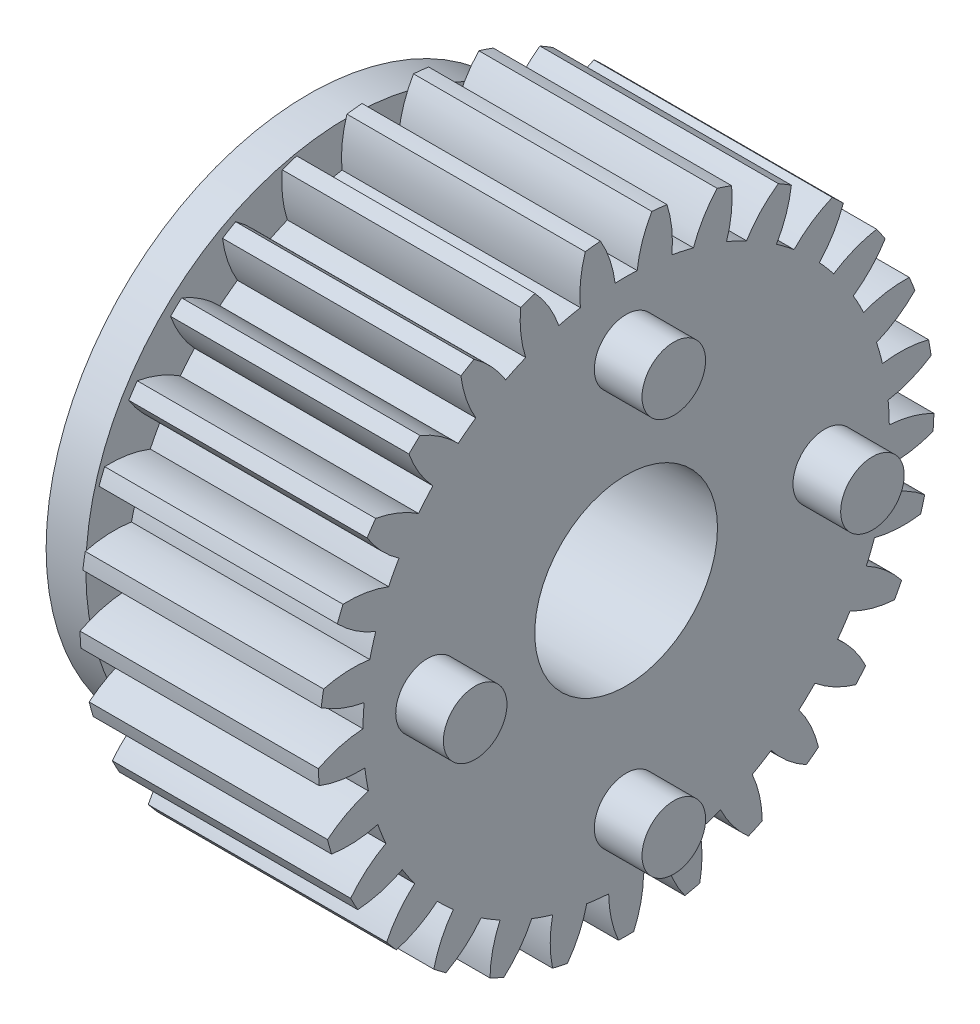
SolidWorks part; units mm, degrees
ref_plane "Plane1" through (0, 0, 0) normal (0, 0, 1) x (1, 0, 0)
ref_plane "Plane2" through (0, 0, 0) normal (0, 1, 0) x (1, 0, 0)
ref_plane "Plane3" through (0, 0, 0) normal (1, 0, 0) x (0, 0, -1)
other "Configuration Table"
sketch "HoldingSke" plane through (0, 0, 0) normal (0, 1, 0) x (1, 0, 0)
  line L0 (0, 0) -> (0.3498, -0.1939)
  line L1 (-15, 0) -> (100, 0) construction
  line L2 (0, 0) -> (-2.1039, 2.3779)
  line L3 (0, 0) -> (-11.863, 4.5341)
  line L4 (0, 0) -> (7.5532, 4.1868)
  line L5 (0, 0) -> (-46.8476, -17.4728)
  line L6 (0, 0) -> (-24.8689, -16.7791)
  line L7 (-2.1039, 2.3779) -> (8.6586, 51.2059)
  line L8 (-76.2, 54.61) -> (-73.9, 54.61)
  line L9 (-67.7845, 28.3722) -> (-49.3413, 33.142)
  line L10 (-76.2, 71.12) -> (104.1128, 71.12)
  line L11 (0, 0) -> (-30, 0)
  line L12 (-76.2, 101.6) -> (-76.113, 101.6)
  line L13 (24.9733, 27.94) -> (52.9518, 28.4284)
  line L14 (24.9733, 27.94) -> (24.9743, 27.94)
  line L15 (24.9733, 27.94) -> (100.4006, 29.5858)
  line L16 (-63.627, -2.5) -> (-12.827, -2.5)
  circle A0 centre (0, 0) radius 6
  circle A1 centre (0, 0) radius 33.124
  circle A2 centre (0, 0) radius 37.5
  circle A3 centre (0, 0) radius 6
  dimension "MHD" = 66.248
  dimension "Hub_dia" = 75
  dimension "Bore" = 12
  dimension "MBD" = 12
  dimension "Num_teeth" = 29
  dimension "Pitch" = 0.4
  dimension "Overall_len" = 50
  dimension "Show_teeth" = 29
  dimension "Thickness" = 30
  dimension "OAL" = 50.0001
  dimension "T_dim" = 2.3
  dimension "Ap" = 14.5
  dimension "H" = 19.05
  dimension "Pitch_radius" = 180.3128
  dimension "Width" = 30
  dimension "Backlash" = 0.087
  dimension "Addendum_fac" = 1
  dimension "Dedendum_fac" = 1.25
  dimension "Clearance_fac" = 0.25
  dimension "Dedendum_add" = 0.001
  dimension "Module" = 2.5
sketch "BasProSke" plane through (0, 0, 0) normal (0, 1, 0) x (1, 0, 0)
  line L0 (-10, 0) -> (60, 0) construction
  line L1 (0, 0) -> (0, 38.75)
  line L2 (0, 0) -> (30, 0)
  line L3 (30, 0) -> (30, 38.75)
  line L4 (30, 38.75) -> (0, 38.75)
  dimension "Thickness" = 30
  dimension "Diameter" = 77.5
revolve "Base-Revolve" add sketch "BasProSke" angle 360 about L0
sketch "TooCutSke" plane through (0, 0, 0) normal (1, 0, 0) x (0, 0, -1)
  line L1 (0, 0) -> (0, 107) construction
  line L2 (0, 0) -> (-2.1148, 36.1883) construction
  line L3 (0, 0) -> (-7.8288, 71.9851) construction
  line L4 (-2.1148, 36.1883) -> (-3.9144, 35.9925) construction
  arc A0 (1.3883, 33.0949) -> (-1.3883, 33.0949) centre (0, 0) ccw
  arc A1 (3.2498, 38.639) -> (-3.2498, 38.639) centre (0, 0) ccw
  circle A2 centre (0, 0) radius 36.25 construction
  circle A3 centre (0, 0) radius 35.0954 construction
  arc A4 (-1.3883, 33.0949) -> (-3.2498, 38.639) centre (-15.7825, 31.3464) ccw
  arc A5 (3.2498, 38.639) -> (1.3883, 33.0949) centre (15.7825, 31.3464) ccw
  dimension "Root_dia" = 66.248
  dimension "Overcut_dia" = 77.5508
  dimension "Pitch_dia" = 72.5
  dimension "Base_dia" = 70.1907
  dimension "Flank_rad" = 14.5
  dimension "Half_ang" = 6.207
  dimension "Half_CT" = 1.8103
extrude "ToothCut" cut sketch "TooCutSke" along normal through all
fillet "Breaks" [suppressed] radius 0.05
fillet "RootFillets" [suppressed] radius 0.626
pattern_circular "TeethCuts" count 29 every 12.414 about axis through (-10, 0, 0) along (1, 0, 0) of "ToothCut", "RootFillets", "Breaks"
sketch "HubNeaOneSke" plane through (0, 0, 0) normal (-1, 0, 0) x (0, 0, 1)
  circle A0 centre (0, 0) radius 33.124
  dimension "Diameter" = 66.248
extrude "HubNearOne" [suppressed] add sketch "HubNeaOneSke" along normal blind 20.0001
sketch "HubNeaBotSke" plane through (0, 0, 0) normal (-1, 0, 0) x (0, 0, 1)
  circle A0 centre (0, 0) radius 33.124
  dimension "Diameter" = 66.248
extrude "HubNearBoth" [suppressed] add sketch "HubNeaBotSke" along normal blind 10
ref_plane "FarPln" through (30, 0, 0) normal (1, 0, 0) x (0, 0, -1)
sketch "HubFarSke" plane through (30, 0, 0) normal (1, 0, 0) x (0, 0, -1)
  circle A0 centre (0, 0) radius 33.124
  dimension "Diameter" = 66.248
extrude "HubFar" [suppressed] add sketch "HubFarSke" along normal blind 10
sketch "BorSke" plane through (0, 0, 0) normal (1, 0, 0) x (0, 0, -1)
  circle A0 centre (0, 0) radius 6
  dimension "Diameter" = 12
extrude "Bore" cut sketch "BorSke" along normal mid plane 100.0001
sketch "KeySke" plane through (0, 0, 0) normal (1, 0, 0) x (0, 0, -1)
  line L0 (-2.5, 0) -> (-2.5, 8.3)
  line L1 (-2.5, 8.3) -> (2.5, 8.3)
  line L2 (2.5, 8.3) -> (2.5, 0)
  line L3 (0, 0) -> (0, 34) construction
  line L4 (-2.5, 0) -> (2.5, 0)
  dimension "Offset" = 8.3
  dimension "Width" = 5
extrude "Keyway" [suppressed] cut sketch "KeySke" along normal mid plane 100.0001
pattern_circular "Keyway2" [suppressed] count 2 every 90 about axis through (-10, 0, 0) along (1, 0, 0)
sketch "Esquisse1" plane through (30, 0, 0) normal (1, 0, 0) x (0, 0, -1)
  circle A0 centre (0, 0) radius 25
  circle A1 centre (0, 25) radius 4
  circle A2 centre (-25, 0) radius 4
  circle A3 centre (25, 0) radius 4
  circle A4 centre (0, -25) radius 4
  dimension "D1" = 8
extrude "Boss.-Extru.1" add sketch "Esquisse1" along normal blind 6 contours A1 | A2 | A4 | A3
sketch "Esquisse2" plane through (30, 0, 0) normal (1, 0, 0) x (0, 0, -1)
  circle A0 centre (0, 0) radius 11.5
extrude "Enlèv. mat.-Extru.1" cut sketch "Esquisse2" against normal through all
sketch "Esquisse3" plane through (0, 0, 0) normal (-1, 0, 0) x (0, 0, 1)
  circle A0 centre (0, 0) radius 23
  circle A1 centre (0, 0) radius 8
extrude "Boss.-Extru.2" add sketch "Esquisse3" along normal blind 5 contours A0 | A1
sketch "Esquisse4" plane through (-5, 0, 0) normal (-1, 0, 0) x (0, 0, 1)
  circle A0 centre (0, 0) radius 33
  circle A1 centre (0, 0) radius 8
extrude "Boss.-Extru.3" add sketch "Esquisse4" along normal blind 5
equation "' \"Module@HoldingSke\" = 6.35"
equation "' \"Num_teeth@HoldingSke\" = 12"
equation "' \"Ap@HoldingSke\" =  20"
equation "' \"Ap@HoldingSke\" = 20"
equation "' \"Width@HoldingSke\" = 0.5 * 25.4"
equation "' \"Hub_dia@HoldingSke\"= 1 * 25.4"
equation "' \"Hub_dia@HoldingSke\" = 1 * 25.4"
equation "' \"Overall_len@HoldingSke\" = 1.0 * 25.4"
equation "' \"Bore@HoldingSke\" = 0.75 * 25.4"
equation "' \"T_dim@HoldingSke\" = 0.1 * 25.4"
equation "' \"Width@KeySke\" = 0.25 * 25.4"
equation "' \"Show_teeth@HoldingSke\" = 13"
equation "' \"Backlash@HoldingSke\" = 0.009 * 25.4"
equation "' \"Addendum_fac@HoldingSke\" = 1.0"
equation "' \"Dedendum_fac@HoldingSke\" = 1.25"
equation "' \"Dedendum_add@HoldingSke\" = 0.00005 * 25.4"
equation "' \"Clearance_fac@HoldingSke\" = 0.25"
equation "\"Pitch@HoldingSke\" = 1 / \"Module@HoldingSke\""
equation "\"Overcut_dia@TooCutSke\" = (\"Num_teeth@HoldingSke\" + 2 * \"Addendum_fac@HoldingSke\") / \"Pitch@HoldingSke\" + 0.002 * 25.4"
equation "\"Pitch_dia@TooCutSke\" = \"Num_teeth@HoldingSke\" / \"Pitch@HoldingSke\""
equation "\"Base_dia@TooCutSke\" = \"Num_teeth@HoldingSke\" / \"Pitch@HoldingSke\" * cos((\"Ap@HoldingSke\"  * 3.14159265 / 180))"
equation "\"Root_dia@TooCutSke\" = (\"Num_teeth@HoldingSke\" + 2) / \"Pitch@HoldingSke\" - 2 * (\"Addendum_fac@HoldingSke\" + \"Dedendum_fac@HoldingSke\") / \"Pitch@HoldingSke\" - \"Dedendum_add@HoldingSke\" * 2"
equation "\"Half_ang@TooCutSke\" = 180 / \"Num_teeth@HoldingSke\""
equation "\"Half_CT@TooCutSke\" = \"Num_teeth@HoldingSke\" / \"Pitch@HoldingSke\" * sin((3.14159265 / 2 / \"Num_teeth@HoldingSke\")) / 2 - 7 * \"Backlash@HoldingSke\" / 4"
equation "\"Flank_rad@TooCutSke\" = \"Num_teeth@HoldingSke\" / \"Pitch@HoldingSke\" / 5"
equation "\"Radius@RootFillets\" = \"Clearance_fac@HoldingSke\" / \"Pitch@HoldingSke\" + \"Dedendum_add@HoldingSke\""
equation "\"Break_rad@Breaks\" = 0.02 / \"Pitch@HoldingSke\""
equation "\"Thickness@HoldingSke\" = \"Width@HoldingSke\""
equation "\"OAL@HoldingSke\" = \"Thickness@HoldingSke\""
equation "\"MHD@HoldingSke\" = (\"Num_teeth@HoldingSke\" + 2) / \"Pitch@HoldingSke\" - 2 * (\"Addendum_fac@HoldingSke\" + \"Dedendum_fac@HoldingSke\")  / \"Pitch@HoldingSke\" - \"Dedendum_add@HoldingSke\" * 2"
equation "\"MBD@HoldingSke\" = (\"Num_teeth@HoldingSke\" + 2) / \"Pitch@HoldingSke\" - 2 * (\"Addendum_fac@HoldingSke\" + \"Dedendum_fac@HoldingSke\")  / \"Pitch@HoldingSke\" - \"Dedendum_add@HoldingSke\" * 2 - 0.002 * 25.4"
equation "\"MHD@HoldingSke\" = ((sgn( \"MHD@HoldingSke\" - \"Hub_dia@HoldingSke\" )-1)*( \"MHD@HoldingSke\" - \"Hub_dia@HoldingSke\" ))/-2+ \"Hub_dia@HoldingSke\""
equation "\"MBD@HoldingSke\" = ((sgn( \"MBD@HoldingSke\" - \"Bore@HoldingSke\" )-1)*( \"MBD@HoldingSke\" - \"Bore@HoldingSke\" ))/-2+ \"Bore@HoldingSke\""
equation "\"OAL@HoldingSke\" = ((sgn( \"OAL@HoldingSke\" - \"Overall_len@HoldingSke\" )+1)*( \"OAL@HoldingSke\" - \"Overall_len@HoldingSke\" ))/2 + \"Overall_len@HoldingSke\" + 0.000002 * 25.4"
equation "\"Num_teeth@TeethCuts\" = int( \"Show_teeth@HoldingSke\" ) + 1"
equation "\"Num_teeth@TeethCuts\" = ((sgn( \"Num_teeth@TeethCuts\" - \"Num_teeth@HoldingSke\" )-1)*( \"Num_teeth@TeethCuts\" - \"Num_teeth@HoldingSke\" ))/-2+ \"Num_teeth@HoldingSke\""
equation "\"Num_teeth@TeethCuts\" = ((sgn( \"Num_teeth@TeethCuts\" - 2.0)+1)*( \"Num_teeth@TeethCuts\" - 2.0))/2 +2.0"
equation "\"Angle@TeethCuts\" = 360.0 / \"Num_teeth@HoldingSke\""
equation "\"Diameter@BasProSke\" = (\"Num_teeth@HoldingSke\" + 2 * \"Addendum_fac@HoldingSke\") / \"Pitch@HoldingSke\""
equation "\"Thickness@BasProSke\"  = \"Thickness@HoldingSke\""
equation "' \"Fillet_rad@BasProSke\" =  \"Thickness@HoldingSke\" * 0.05"
equation "' \"Fillet_rad@BasProSke\" = \"Thickness@HoldingSke\" * 0.05"
equation "\"MHD@HoldingSke\" = ((sgn( \"MHD@HoldingSke\" - \"Root_dia@TooCutSke\" )-1)*( \"MHD@HoldingSke\" - \"Root_dia@TooCutSke\" ))/-2+ \"Root_dia@TooCutSke\""
equation "\"Diameter@HubNeaOneSke\" = \"MHD@HoldingSke\""
equation "\"Length@HubNearOne\" = \"OAL@HoldingSke\" - \"Thickness@BasProSke\""
equation "\"Diameter@HubNeaBotSke\" = \"MHD@HoldingSke\""
equation "\"Length@HubNearBoth\" = ( \"OAL@HoldingSke\" - \"Thickness@BasProSke\" ) / 2.0"
equation "\"Thickness@FarPln\" = \"Thickness@BasProSke\""
equation "\"Diameter@HubFarSke\" = \"MHD@HoldingSke\""
equation "\"Length@HubFar\" = ( \"OAL@HoldingSke\" - \"Thickness@BasProSke\" ) / 2.0"
equation "\"Diameter@BorSke\" = \"MBD@HoldingSke\""
equation "\"D1@Bore\" = \"OAL@HoldingSke\" * 2.0"
equation "\"D1@Keyway\" = \"OAL@HoldingSke\" * 2.0"
equation "\"Offset@KeySke\" = \"T_dim@HoldingSke\" + \"MBD@HoldingSke\" / 2.0"
